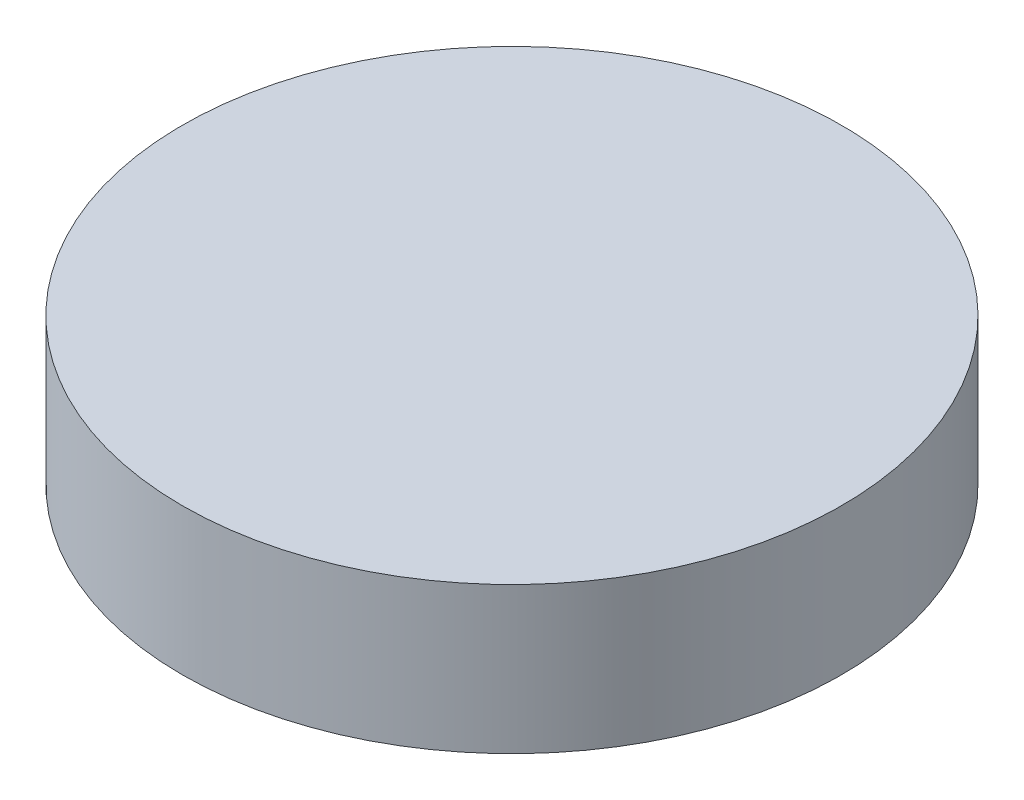
SolidWorks part; units mm, degrees
material "玻璃"
ref_plane "前视基准面" through (0, 0, 0) normal (0, 0, 1) x (1, 0, 0)
ref_plane "上视基准面" through (0, 0, 0) normal (0, 1, 0) x (1, 0, 0)
ref_plane "右视基准面" through (0, 0, 0) normal (1, 0, 0) x (0, 0, -1)
sketch "草图1" plane through (0, 0, 0) normal (0, 1, 0) x (1, 0, 0)
  circle A0 centre (0, 0) radius 0.9
  dimension "D1" = 1.8
extrude "凸台-拉伸1" add sketch "草图1" along normal blind 0.4
